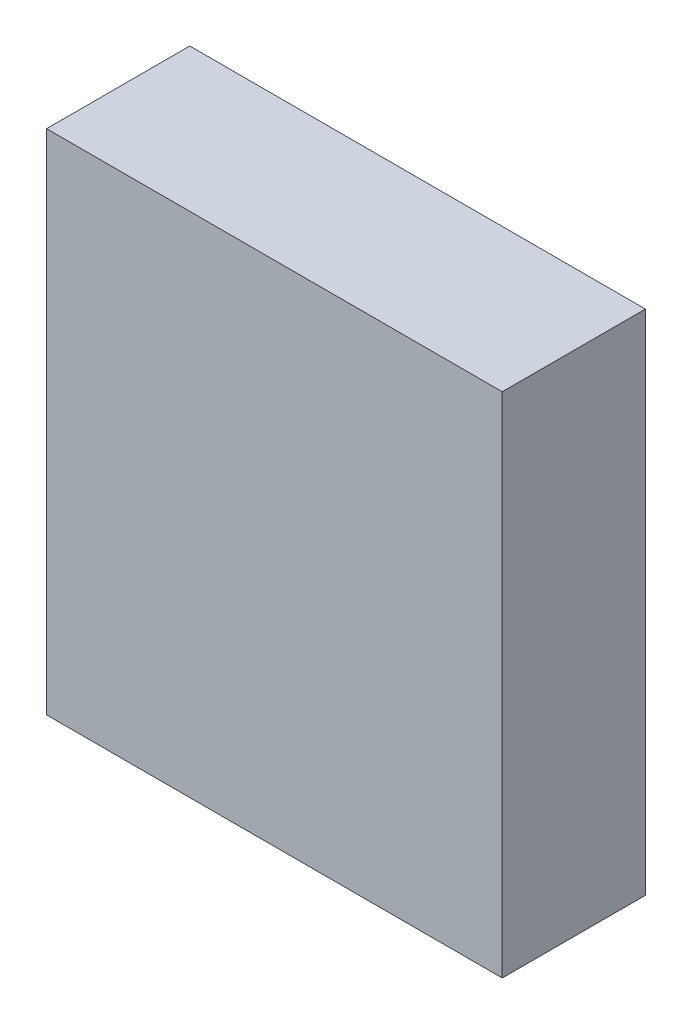
SolidWorks part; units mm, degrees
ref_plane "前视基准面" through (0, 0, 0) normal (0, 0, 1) x (1, 0, 0)
ref_plane "上视基准面" through (0, 0, 0) normal (0, 1, 0) x (1, 0, 0)
ref_plane "右视基准面" through (0, 0, 0) normal (1, 0, 0) x (0, 0, -1)
sketch "草图1" plane through (0, 0, 0) normal (0, 0, 1) x (1, 0, 0)
  line L0 (-0.875, -0.975) -> (0.875, -0.975)
  line L1 (0.875, -0.975) -> (0.875, 0.975)
  line L2 (0.875, 0.975) -> (-0.875, 0.975)
  line L3 (-0.875, 0.975) -> (-0.875, -0.975)
extrude "凸台-拉伸1" add sketch "草图1" along normal blind 0.55 from offset 0
